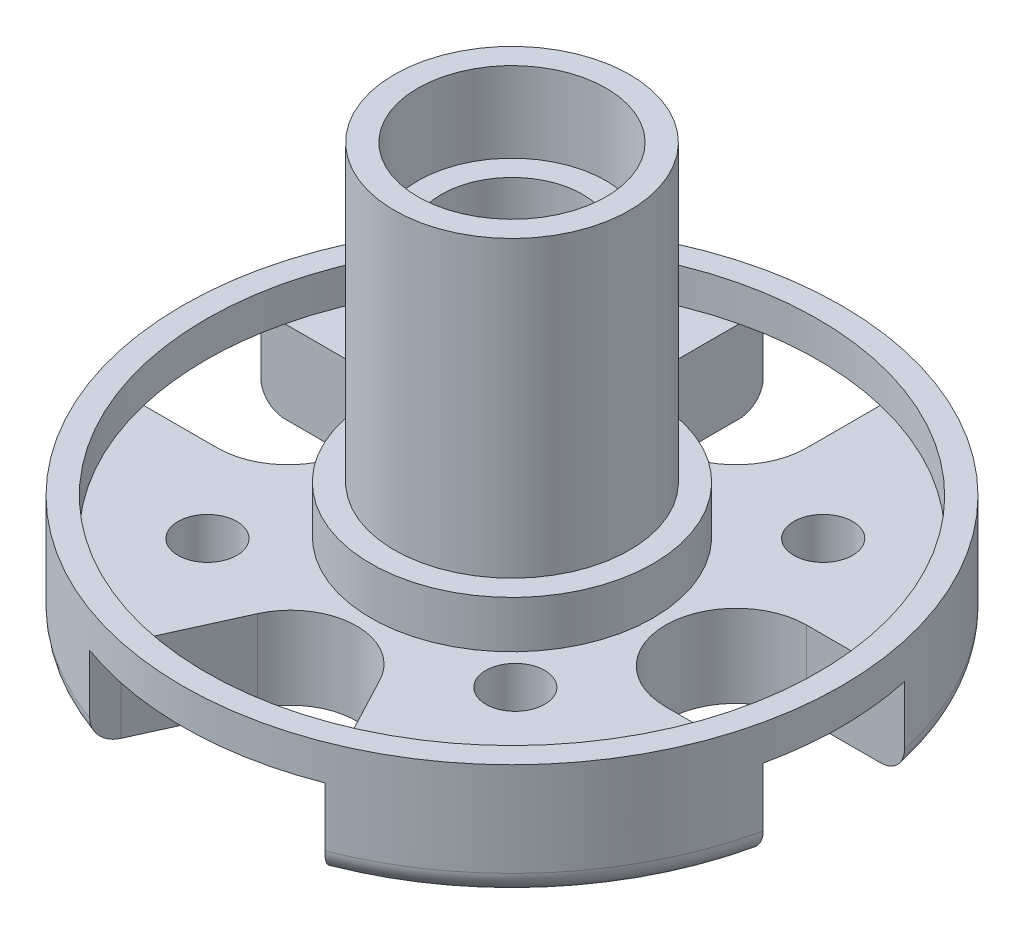
SolidWorks part; units mm, degrees
material "Fonte grise (SN)"
ref_plane "Plan de face" through (0, 0, 0) normal (0, 0, 1) x (1, 0, 0)
ref_plane "Plan de dessus" through (0, 0, 0) normal (0, 1, 0) x (1, 0, 0)
ref_plane "Plan de droite" through (0, 0, 0) normal (1, 0, 0) x (0, 0, -1)
sketch "Esquisse3" plane through (0, 0, 0) normal (0, 0, 1) x (1, 0, 0)
  line L1 (-12.975, -8.821) -> (-12.975, -3.821)
  line L2 (-12.975, -3.821) -> (-11.975, -3.821)
  line L3 (-11.975, -3.821) -> (-11.975, -5.321)
  line L4 (-11.975, -5.321) -> (-4.975, -5.321)
  line L5 (-4.975, -5.321) -> (-4.975, -3.321)
  line L8 (-3.975, 9.179) -> (-2.975, 9.179)
  line L9 (-2.975, 9.179) -> (-2.975, 5.7705)
  line L11 (4.025, 5.7705) -> (4.025, -4.821) construction
  line L12 (4.025, -4.821) -> (5.025, -4.821) construction
  line L13 (5.025, -4.821) -> (5.025, -8.821) construction
  line L15 (-4.975, -3.321) -> (-3.975, -3.321)
  line L16 (-3.975, -3.321) -> (-3.975, 9.179)
  line L17 (1.025, 13.7439) -> (1.025, -15.6106) construction
  line L18 (6.025, -3.321) -> (6.025, 9.179) construction
  line L19 (7.025, -3.321) -> (6.025, -3.321) construction
  line L21 (-2.975, -4.821) -> (-2.975, -8.821)
  line L22 (-1.975, -4.821) -> (-2.975, -4.821)
  line L23 (-1.975, 5.7705) -> (-1.975, -4.821)
  line L25 (5.025, 9.179) -> (5.025, 5.7705) construction
  line L26 (6.025, 9.179) -> (5.025, 9.179) construction
  line L27 (7.025, -5.321) -> (7.025, -3.321) construction
  line L28 (14.025, -5.321) -> (7.025, -5.321) construction
  line L29 (14.025, -3.821) -> (14.025, -5.321) construction
  line L30 (15.025, -3.821) -> (14.025, -3.821) construction
  line L31 (15.025, -8.821) -> (15.025, -3.821) construction
  line L33 (-2.975, 5.7705) -> (-1.975, 5.7705)
  line L34 (4.025, 5.7705) -> (5.025, 5.7705) construction
  line L35 (-12.975, -8.821) -> (-2.975, -8.821)
  line L36 (5.025, -8.821) -> (15.025, -8.821) construction
  dimension "D1" = 8
  dimension "D2" = 10
  dimension "D3" = 12
  dimension "D4" = 26
  dimension "D5" = 28
  dimension "D6" = 4
  dimension "D7" = 2
  dimension "D8" = 5
  dimension "D9" = 1.5
  dimension "D10" = 13
  dimension "D11" = 6
  dimension "D12" = 8
revolve "Révolution1" add sketch "Esquisse3" angle 360 about L17
fillet "Congé1" radius 1 1 edges at (-12.975, -8.821, 0)
sketch "Esquisse5" plane through (0, -8.821, 0) normal (0, -1, 0) x (1, 0, 0)
  line L0 (1.1467, 0) -> (16.6616, 0) construction
  line L1 (1.1467, 0) -> (1.1467, 7.5423) construction
  line L2 (13.6741, 3) -> (10.5467, 3)
  line L3 (13.6741, -3) -> (10.5467, -3)
  line L4 (13.6741, 3) -> (14.6998, 3)
  line L5 (13.6741, -3) -> (14.6998, -3)
  line L6 (14.6998, 3) -> (15.0311, 3)
  line L7 (14.6998, -3) -> (15.0311, -3)
  circle A0 centre (1.025, 0) radius 13 construction
  arc A1 (10.5467, 3) -> (10.5467, -3) centre (10.5467, 0) ccw
  circle A2 centre (1.025, 0) radius 14 construction
  arc A4 (15.0311, 3) -> (15.0311, -3) centre (1.1467, 0) cw
  dimension "D1" = 9.4
  dimension "D2" = 9.4
  dimension "D3" = 3
  dimension "D4" = 3
extrude "Enlèv. mat.-Extru.1" cut sketch "Esquisse5" against normal up to surface (3.5 mm away) up to face at (-11.975, -5.321, 0)
pattern_circular "Répétition circulaire2" count 3 every 90 about axis through (1.025, 0, 0) along (0, 1, 0) of "Enlèv. mat.-Extru.1"
sketch "Esquisse7" plane through (0, -8.821, 0) normal (0, -1, 0) x (1, 0, 0)
  line L0 (1.025, 0) -> (1.025, 14.3776) construction
  line L1 (-3.356, 12.2395) -> (-1.5415, 8.2395)
  line L2 (5.644, 12.1518) -> (3.533, 8.1518)
  line L3 (1.025, 0) -> (14.3404, 0) construction
  line L4 (-3.356, 12.2395) -> (-4.2769, 14.3421)
  line L5 (5.644, 12.1518) -> (6.7199, 14.1906)
  arc A0 (13.6741, 3) -> (-11.6241, 3) centre (1.025, 0) ccw construction
  arc A1 (-1.5415, 8.2395) -> (3.533, 8.1518) centre (1.0166, 9.4) ccw
  arc A2 (-4.2769, 14.3421) -> (6.7199, 14.1906) centre (1.025, 0) cw
  dimension "D1" = 4
  dimension "D2" = 4
  dimension "D3" = 9
  dimension "D4" = 9.4
extrude "Enlèv. mat.-Extru.2" cut sketch "Esquisse7" against normal up to surface (3.5 mm away)
sketch "Esquisse26" plane through (0, -5.321, 0) normal (0, 1, 0) x (1, 0, 0)
  line L0 (0.4469, 0) -> (17.358, 0) construction
  line L1 (17.358, 0) -> (-13.3001, 0) construction
  line L2 (1.1658, 0) -> (1.1658, 20.7552) construction
  line L3 (1.1658, 20.7552) -> (1.1658, -16.5566) construction
  line L4 (1.1658, 0) -> (12.3811, 11.2153) construction
  line L5 (1.1658, 0) -> (-10.7197, -11.8856) construction
  line L6 (1.1658, 0) -> (-10.0471, 11.213) construction
  line L7 (1.1658, 0) -> (11.2972, -10.1314) construction
hole_wizard "Trou taraudé M3x0.52" positions "Esquisse3D6" profile "Esquisse32" tap size "M3x0.5" standard "Ansi Metric" end condition through all
sketch3d "Esquisse3D6"
  line L0 (1.1658, -5.321, 0) -> (-10.7197, -5.321, 11.8856) construction
  line L1 (1.1658, -5.321, 0) -> (-10.0471, -5.321, -11.213) construction
  line L2 (1.1658, -5.321, 0) -> (11.2972, -5.321, 10.1314) construction
  line L3 (1.1658, -5.321, 0) -> (12.3811, -5.321, -11.2153) construction
  point P0 (-5.3749, -5.321, 6.5407)
  point P4 (-4.3142, -5.321, -5.4801)
  point P8 (6.6459, -5.321, 5.4801)
  point P12 (7.7066, -5.321, -6.5407)
  dimension "D1" = 9.25
  dimension "D2" = 9.25
  dimension "D3" = 7.75
  dimension "D4" = 7.75
sketch "Esquisse32" plane through (-5.3749, -5.321, 6.5407) normal (1, 0, 0) x (0, 0, 1)
  line L0 (0, 0) -> (0, 3.5)
  line L1 (0, 3.5) -> (1.25, 3.5)
  line L2 (1.25, 3.5) -> (1.25, 0)
  line L5 (1.25, 0) -> (0, 0)
  line L11 (0, -6.35) -> (0, 107.95) construction
  dimension "Diamètre du trou pour taraudage jusqu'au prochain" = 2.5
  dimension "Profondeur du trou pour taraudage jusqu'au prochain" = 3.5
cosmetic thread "Filetage de perçage9" parameters "D2"=3
cosmetic thread "Filetage de perçage10" parameters "D2"=3
cosmetic thread "Filetage de perçage11" parameters "D2"=3
cosmetic thread "Filetage de perçage12" parameters "D2"=3
